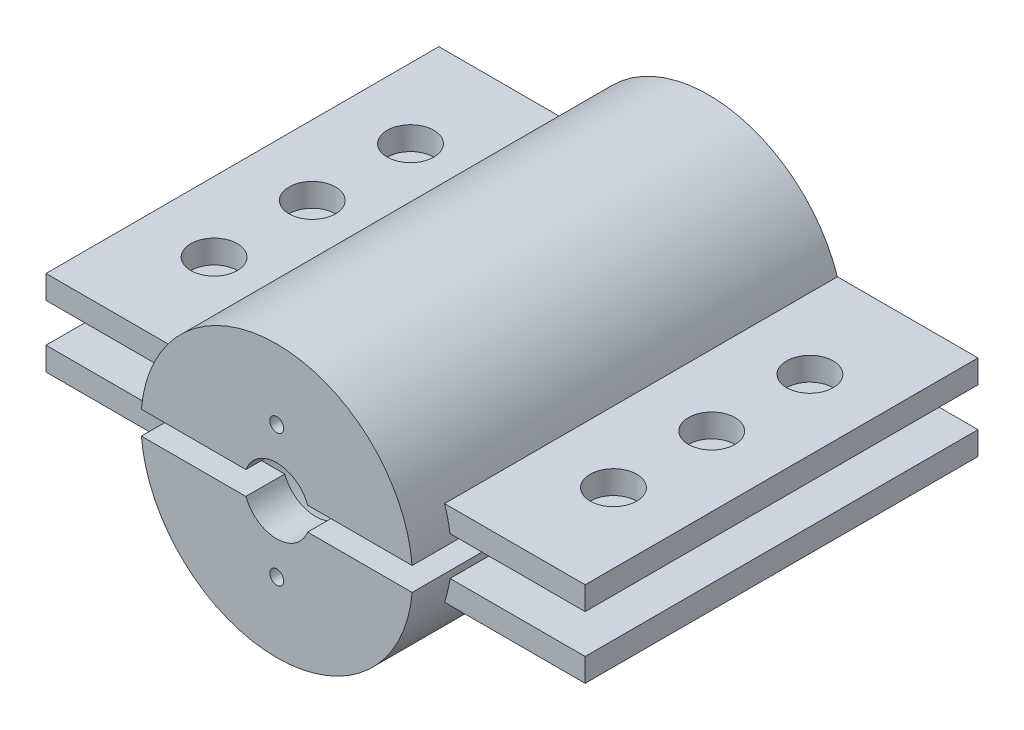
SolidWorks part; units mm, degrees
ref_plane "Plano frontal" through (0, 0, 0) normal (0, 0, 1) x (1, 0, 0)
ref_plane "Plano superior" through (0, 0, 0) normal (0, 1, 0) x (1, 0, 0)
ref_plane "Plano direito" through (0, 0, 0) normal (1, 0, 0) x (0, 0, -1)
sketch "Esboço1" plane through (0, 0, 0) normal (0, 0, 1) x (1, 0, 0)
  circle A0 centre (0, 0) radius 12.5
  circle A1 centre (0, 0) radius 17.5
  dimension "D1" = 25
  dimension "D2" = 35
extrude "Ressalto-extrusão1" add sketch "Esboço1" along normal blind 55.6
ref_plane "Plano1" through (0, 0, 55.6) normal (0, 0, 1) x (1, 0, 0)
sketch "Esboço2" plane through (0, 0, 55.6) normal (0, 0, 1) x (1, 0, 0)
  circle A0 centre (0, 0) radius 12.5
extrude "Ressalto-extrusão2" add sketch "Esboço2" against normal blind 5
sketch "Esboço4" plane through (0, 0, 55.6) normal (0, 0, 1) x (1, 0, 0)
  circle A1 centre (0, 0) radius 12.1
  circle A2 centre (0, 0) radius 17.5
  dimension "D1" = 24.2
extrude "Ressalto-extrusão3" add sketch "Esboço4" against normal blind 34.8
sketch "Esboço5" [suppressed] plane through (0, 0, 0) normal (0, 0, 1) x (1, 0, 0)
  line L1 (-8.9, 0) -> (-8.9, 3)
  line L2 (-8.9, 3) -> (8.9, 3)
  line L3 (8.9, 3) -> (8.9, -3)
  line L4 (8.9, -3) -> (-8.9, -3)
  line L5 (-8.9, -3) -> (-8.9, 3)
  line L6 (-8.9, 0) -> (-8.9, -3)
extrude "Corte-extrusão1" [suppressed] cut sketch "Esboço5" along normal blind 80.8 contours L5 L4 L3 L2 L1
sketch "Esboço6" [suppressed] plane through (0, 0, 55.6) normal (0, 0, 1) x (1, 0, 0)
  line L0 (17.5, 0) -> (17.5, 1.5)
  line L1 (17.5, 0) -> (17.5, -1.5)
  line L2 (17.5, 1.5) -> (27.5, 1.5)
  line L3 (27.5, 1.5) -> (27.5, 4.5)
  line L4 (27.5, 4.5) -> (13.5, 4.5)
  line L5 (13.5, 4.5) -> (13.5, 1.5)
  line L6 (13.5, 1.5) -> (17.5, 1.5)
  line L7 (17.4486, -4.5) -> (27.5, -4.5)
  line L8 (27.5, -4.5) -> (27.5, -1.5)
  line L9 (27.5, -1.5) -> (13.5, -1.5)
  line L10 (13.5, -1.5) -> (13.5, -4.5)
  line L11 (13.5, -4.5) -> (17.4486, -4.5)
  line L12 (-17.5, 0) -> (-17.5, 1.5)
  line L13 (-17.5, 0) -> (-17.5, -1.5)
  line L15 (-13.5, 1.5) -> (-13.5, 4.5)
  line L16 (-13.5, 4.5) -> (-27.5, 4.5)
  line L17 (-27.5, 4.5) -> (-27.5, 1.5)
  line L19 (-27.5, 1.5) -> (-13.5, 1.5)
  line L20 (-13.5, 1.5) -> (-17.5, 1.5)
  line L22 (-13.5, -4.5) -> (-13.5, -1.5)
  line L23 (-13.5, -1.5) -> (-27.5, -1.5)
  line L24 (-27.5, -1.5) -> (-27.5, -4.5)
  line L26 (-27.5, -4.5) -> (-13.5, -4.5)
  line L27 (-13.5, -1.5) -> (-17.5, -1.5)
  circle A0 centre (0, 0) radius 17.5 construction
  dimension "D1" = 3
  dimension "D2" = 14
  dimension "D3" = 3
  dimension "D4" = 14
  dimension "D5" = 1.5
  dimension "D6" = 1.5
  dimension "D7" = 4
  dimension "D8" = 4
  dimension "D9" = 4
sketch "Esboço12" plane through (0, 0, 55.6) normal (0, 0, 1) x (1, 0, 0)
  line L3 (0, 1.5) -> (17.4356, 1.5)
  line L4 (0, 1.5) -> (-17.4356, 1.5)
  line L5 (0, -1.5) -> (-17.4356, -1.5)
  line L6 (0, -1.5) -> (17.4356, -1.5)
  circle A0 centre (0, 0) radius 17.5 construction
  arc A1 (-17.4356, 1.5) -> (-17.4356, -1.5) centre (0, 0) ccw
  arc A2 (17.4356, -1.5) -> (17.4356, 1.5) centre (0, 0) ccw
extrude "Corte-extrusão4" cut sketch "Esboço12" against normal blind 5
sketch "Esboço13" plane through (0, 0, 0) normal (0, 0, 1) x (1, 0, 0)
  line L0 (0, 0) -> (0, -15.4285)
  circle A0 centre (0, -7.7143) radius 2
  dimension "D1" = 4
extrude "Corte-extrusão6" cut sketch "Esboço13" along normal blind 78 contours A0
ref_plane "Plano6" through (0, 0, 50.6) normal (0, 0, -1) x (-1, 0, 0)
sketch "Esboço14" plane through (0, 0, 50.6) normal (0, 0, -1) x (-1, 0, 0)
  line L0 (-14.7211, 1.5) -> (-14.7211, 2.5)
  line L1 (-17.4356, 1.5) -> (-12.0067, 1.5) construction
  line L2 (-14.7211, 2.5) -> (-34.7211, 2.5)
  line L3 (-34.7211, 2.5) -> (-34.7211, 5.5)
  line L4 (-34.7211, 5.5) -> (-14.7211, 5.5)
  line L5 (-14.7211, 5.5) -> (-14.7211, 2.5)
  line L6 (-14.7211, 1.5) -> (-14.7211, -1.5)
  line L7 (17.4356, -1.5) -> (-17.4356, -1.5) construction
  line L8 (-14.7211, -1.5) -> (-14.7211, -2.5)
  line L9 (-14.7211, -5.5) -> (-34.7211, -5.5)
  line L10 (-34.7211, -5.5) -> (-34.7211, -2.5)
  line L11 (-34.7211, -2.5) -> (-14.7211, -2.5)
  line L12 (-14.7211, -2.5) -> (-14.7211, -5.5)
  line L13 (14.7211, 1.5) -> (14.7211, 2.5)
  line L14 (12.0067, 1.5) -> (17.4356, 1.5) construction
  line L15 (14.7211, 2.5) -> (14.7211, -2.5)
  line L16 (34.7211, 2.5) -> (14.7211, 2.5)
  line L17 (14.7211, 2.5) -> (14.7211, 5.5)
  line L18 (14.7211, 5.5) -> (34.7211, 5.5)
  line L19 (34.7211, 5.5) -> (34.7211, 2.5)
  line L20 (34.7211, -5.5) -> (14.7211, -5.5)
  line L21 (14.7211, -5.5) -> (14.7211, -2.5)
  line L22 (14.7211, -2.5) -> (34.7211, -2.5)
  line L23 (34.7211, -2.5) -> (34.7211, -5.5)
  dimension "D1" = 1
  dimension "D2" = 3
  dimension "D3" = 20
  dimension "D4" = 1
  dimension "D5" = 20
  dimension "D6" = 1
  dimension "D7" = 3
  dimension "D8" = 20
  dimension "D9" = 1
  dimension "D10" = 3
  dimension "D11" = 20
extrude "Ressalto-extrusão5" add sketch "Esboço14" along normal blind 50.6 contours L23 L22 L21 L20 | L19 L18 L17 L16 | L5 L4 L3 L2 | L12 L11 L10 L9
sketch "Esboço15" plane through (0, 0, 0) normal (0, 1, 0) x (1, 0, 0)
  line L0 (-34.7211, 0) -> (-25.7211, 0)
  line L1 (-16.6132, 0) -> (-34.7211, 0) construction
  line L2 (34.7211, 0) -> (25.7211, 0)
  line L3 (34.7211, 0) -> (16.6132, 0) construction
  line L4 (-25.7211, 0) -> (-25.7211, -50.6) construction
  line L5 (19.25, -50.6) -> (-19.25, -50.6) construction
  line L6 (25.7211, 0) -> (25.7211, -50.6) construction
  line L7 (-25.7211, -25.3) -> (-25.7211, 0) construction
  line L8 (-25.7211, 0) -> (-25.7211, -12.65) construction
  line L9 (-25.7211, -12.65) -> (25.7211, -12.65) construction
  line L10 (25.7211, -12.65) -> (25.7211, -50.6) construction
  line L11 (25.7211, -50.6) -> (25.7211, -25.3) construction
  line L12 (25.7211, -25.3) -> (25.7211, -37.95) construction
  line L13 (25.7211, -37.95) -> (-25.7211, -37.95) construction
  line L14 (-25.7211, -37.95) -> (-25.7211, -50.6) construction
  circle A0 centre (-25.7211, -25.3) radius 3
  circle A1 centre (25.7211, -25.3) radius 3
  circle A2 centre (-25.7211, -37.95) radius 3
  circle A3 centre (-25.7211, -12.65) radius 3
  circle A4 centre (25.7211, -12.65) radius 3
  circle A5 centre (25.7211, -37.95) radius 3
  dimension "D3" = 6
  dimension "D4" = 6
  dimension "D5" = 6
  dimension "D6" = 6
  dimension "D7" = 6
  dimension "D8" = 6
  dimension "D1" = 9
  dimension "D2" = 9
extrude "Corte-extrusão7" cut sketch "Esboço15" against normal blind 50.6 and the other way blind 50.6 contours A2 | A0 | A3 | A4 | A1 | A5
sketch "Esboço16" plane through (0, 0, 0) normal (0, 0, 1) x (1, 0, 0)
  line L0 (0, 17.5) -> (0, -17.5)
  arc A0 (16.6132, 5.5) -> (-16.6132, 5.5) centre (0, 0) ccw construction
  arc A1 (-16.6132, -5.5) -> (16.6132, -5.5) centre (0, 0) ccw construction
sketch "Esboço19" plane through (0, 0, 50.6) normal (0, 0, -1) x (-1, 0, 0)
  line L0 (17.4356, 1.5) -> (17.4356, -1.5)
  line L1 (17.4356, -1.5) -> (20.6849, -1.5)
  line L2 (20.6849, -1.5) -> (20.6849, 1.5)
  line L3 (20.6849, 1.5) -> (17.4356, 1.5)
  line L4 (-17.4356, -1.5) -> (-17.4356, 1.5)
  line L5 (-17.4356, 1.5) -> (-18.4603, 1.5)
  line L6 (-18.4603, 1.5) -> (-18.4603, -1.5)
  line L7 (-18.4603, -1.5) -> (-17.4356, -1.5)
extrude "Corte-extrusão8" cut sketch "Esboço19" along normal blind 78
sketch "Esboço20" plane through (0, 0, 0) normal (0, 1, 0) x (1, 0, 0)
  line L0 (0, -55.6) -> (17.4356, -50.6)
  line L1 (-17.4356, -55.6) -> (17.4356, -55.6) construction
  line L2 (19.25, -50.6) -> (-19.25, -50.6) construction
  line L3 (17.4356, -50.6) -> (17.4356, -55.6)
  line L4 (17.4356, -55.6) -> (0, -55.6)
  line L5 (17.4356, -50.6) -> (25.7211, -37.95)
  line L6 (25.7211, -37.95) -> (25.7211, -50.6)
  line L7 (25.7211, -50.6) -> (17.4356, -50.6)
  line L8 (25.7211, -50.6) -> (25.7211, -55.6)
  line L9 (25.7211, -55.6) -> (17.4356, -55.6)
  line L10 (25.7211, -37.95) -> (25.6672, 0)
  line L11 (25.7211, -61.824) -> (17.4356, -61.824)
  line L12 (34.7211, 0) -> (16.6132, 0) construction
  line L13 (25.6672, 0) -> (25.7211, -12.65)
  line L14 (25.7211, -12.65) -> (25.7211, -25.3)
  line L15 (25.7211, -25.3) -> (25.7211, -37.95)
  dimension "D1" = 8.2855
sketch "Esboço21" plane through (0, 0, 0) normal (0, 0, 1) x (1, 0, 0)
  line L0 (0, 0) -> (17.4356, 0)
  line L1 (0, 17.5) -> (0, -17.5) construction
  line L2 (17.4356, -1.5) -> (17.4356, 1.5) construction
  line L3 (0, 0) -> (-17.4356, 0)
  line L4 (-17.4356, 1.5) -> (-17.4356, -1.5) construction
  dimension "D1" = 34.8712
sketch "Esboço22" plane through (0, 0, 0) normal (0, 0, 1) x (1, 0, 0)
  line L0 (-17.4356, 1.5) -> (-14.7211, 1.5)
  line L1 (-12.0067, 1.5) -> (-17.4356, 1.5) construction
  line L2 (-14.7211, 1.5) -> (-14.7211, -1.5)
  line L3 (-17.4356, -1.5) -> (-12.0067, -1.5) construction
  line L4 (-14.7211, -1.5) -> (-17.4356, -1.5)
  line L5 (-17.4356, -1.5) -> (-17.4356, 1.5)
ref_plane "Plano7" through (0, 0, 0) normal (0, 0, -1) x (-1, 0, 0)
sketch "Esboço24" plane through (0, 0, 0) normal (0, 0, -1) x (-1, 0, 0)
  line L1 (-14.4356, -1.5) -> (-17.4356, -1.5)
  line L2 (-14.4356, -1.5) -> (-14.4356, 1.5)
  line L3 (-14.4356, 1.5) -> (-17.4356, 1.5)
  line L4 (-17.4356, -1.5) -> (-17.4356, 1.5)
  line L5 (17.4356, 1.5) -> (14.4356, 1.5)
  line L6 (17.4356, 1.5) -> (17.4356, -1.5)
  line L7 (17.4356, -1.5) -> (14.4356, -1.5)
  line L8 (14.4356, 1.5) -> (14.4356, -1.5)
  dimension "D1" = 3
  dimension "D2" = 3
extrude "Corte-extrusão9" cut sketch "Esboço24" against normal blind 78
sketch "Esboço25" plane through (0, 0, 0) normal (0, 0, 1) x (1, 0, 0)
  line L0 (-14.4356, 0) -> (14.4356, 0)
  line L1 (-14.4356, -1.5) -> (-14.4356, 1.5) construction
  line L2 (14.4356, 1.5) -> (14.4356, -1.5) construction
  line L4 (-14.4356, -24.6586) -> (14.4356, -24.6586)
  dimension "D1" = 28.8712
sketch "Esboço26" plane through (0, 0, 0) normal (0, 1, 0) x (1, 0, 0)
  line L4 (-25.7211, -12.65) -> (-25.7211, -25.3)
  line L5 (-25.7211, 6.2523) -> (0, 6.2523)
  line L6 (-41.4874, 0) -> (-41.4874, -12.65)
  line L7 (-25.7211, -25.3) -> (-41.4874, -25.3)
  line L8 (-41.4874, -25.3) -> (-41.4874, -12.65)
  dimension "D1" = 25.7211
  dimension "D2" = 12.65
  dimension "D3" = 12.65
ref_plane "Plano8" through (0, 0, 55.6) normal (0, 0, 1) x (1, 0, 0)
sketch "Esboço27" plane through (0, 0, 55.6) normal (0, 0, 1) x (1, 0, 0)
  circle A0 centre (0, 0) radius 4.25
  dimension "D1" = 8.5
extrude "Corte-extrusão10" cut sketch "Esboço27" against normal blind 10
sketch "Esboço28" plane through (0, 0, 55.6) normal (0, 0, 1) x (1, 0, 0)
  circle A0 centre (0, -7.7143) radius 2
extrude "Ressalto-extrusão6" add sketch "Esboço28" against normal blind 5
sketch "Esboço29" plane through (0, 0, 55.6) normal (0, 0, 1) x (1, 0, 0)
  line L0 (0, 0) -> (0, 8.5)
  line L1 (0, 0) -> (0, -8.5)
  circle A0 centre (0, 8.5) radius 0.9
  circle A1 centre (0, -8.5) radius 0.9
  dimension "D2" = 1.8
  dimension "D4" = 1.8
  dimension "D1" = 8.5
  dimension "D3" = 8.5
extrude "Corte-extrusão11" cut sketch "Esboço29" against normal blind 5 contours A0 | A1
